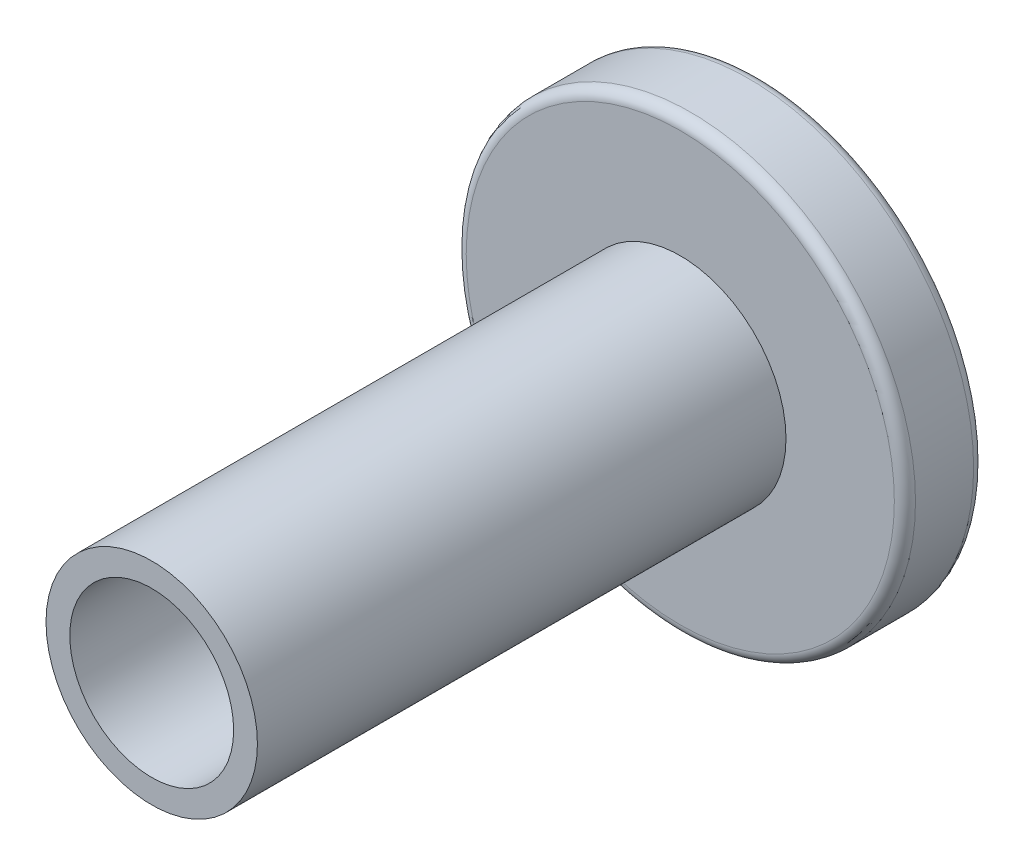
SolidWorks part; units mm, degrees
material "AISI 304"
ref_plane "前视基准面" through (0, 0, 0) normal (0, 0, 1) x (1, 0, 0)
ref_plane "上视基准面" through (0, 0, 0) normal (0, 1, 0) x (1, 0, 0)
ref_plane "右视基准面" through (0, 0, 0) normal (1, 0, 0) x (0, 0, -1)
other "Configuration Table"
sketch "草图1" plane through (0, 0, 0) normal (0, 0, 1) x (1, 0, 0)
  circle A0 centre (0, 0) radius 4.25
  dimension "D1" = 8.5
extrude "凸台-拉伸1" add sketch "草图1" along normal blind 1.5
sketch "草图2" plane through (0, 0, 1.5) normal (0, 0, 1) x (1, 0, 0)
  circle A0 centre (0, 0) radius 2
  circle A1 centre (0, 0) radius 1.55
  dimension "D1" = 4
  dimension "D2" = 3.1
extrude "凸台-拉伸2" add sketch "草图2" along normal blind 10
fillet "圆角1" radius 0.2 2 edges at (4.25, 0, 0) (4.25, 0, 1.5)
sketch "草图3" plane through (0, 0, 0) normal (0, 0, -1) x (-1, 0, 0)
  line L0 (0, 0) -> (1.4434, 0) construction
  line L1 (1.4434, 0) -> (0.7217, 1.25)
  line L2 (0.7217, 1.25) -> (-0.7217, 1.25)
  line L3 (-0.7217, 1.25) -> (-1.4434, 0)
  line L4 (-1.4434, 0) -> (-0.7217, -1.25)
  line L5 (-0.7217, -1.25) -> (0.7217, -1.25)
  line L6 (0.7217, -1.25) -> (1.4434, 0)
  circle A0 centre (0, 0) radius 1.25 construction
  dimension "D1" = 2.5
extrude "切除-拉伸1" cut sketch "草图3" against normal blind 1.5
